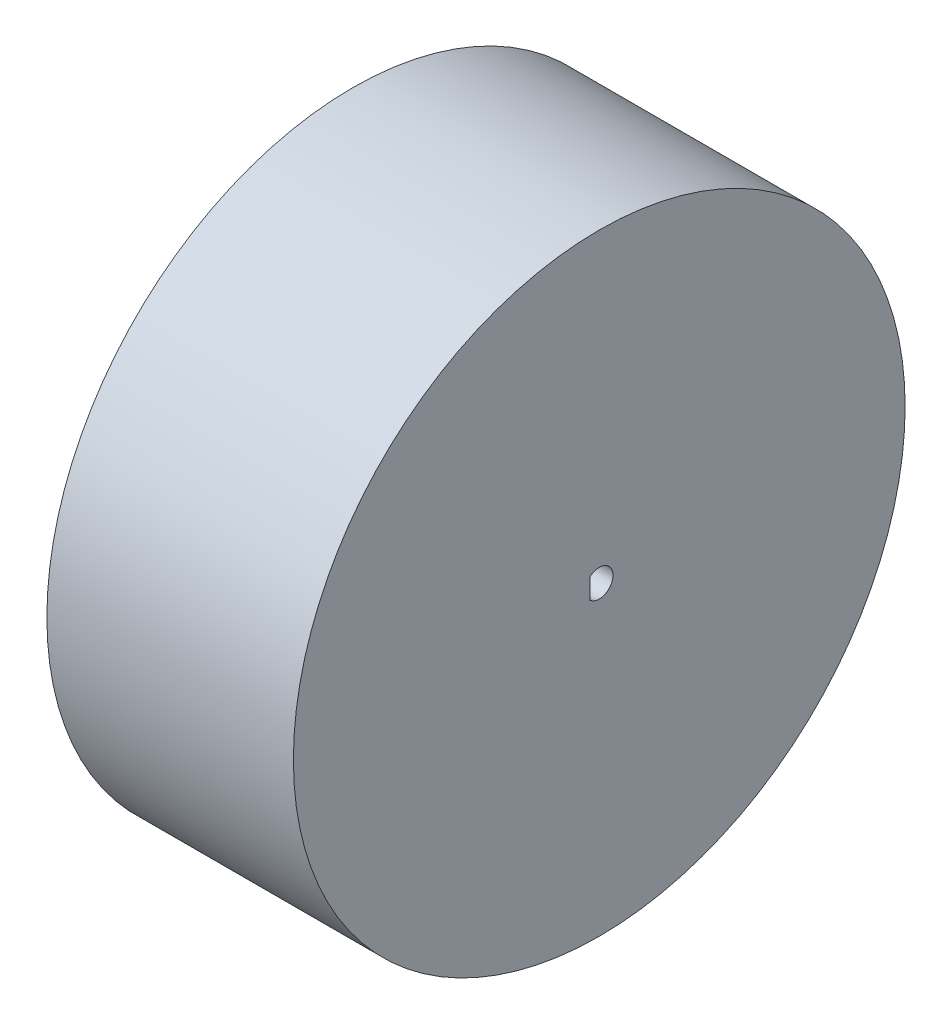
SolidWorks part; units mm, degrees
ref_plane "Front Plane" through (0, 0, 0) normal (0, 0, 1) x (1, 0, 0)
ref_plane "Top Plane" through (0, 0, 0) normal (0, 1, 0) x (1, 0, 0)
ref_plane "Right Plane" through (0, 0, 0) normal (1, 0, 0) x (0, 0, -1)
sketch "Sketch1" plane through (0, 0, 0) normal (1, 0, 0) x (0, 0, -1)
  line L0 (-1, 1.118) -> (-1, -1.118)
  circle A0 centre (0, 0) radius 33.5
  arc A1 (-1, -1.118) -> (-1, 1.118) centre (0, 0) ccw
  dimension "D1" = 67
  dimension "D2" = 1.5
  dimension "D3" = 1
extrude "Boss-Extrude1" add sketch "Sketch1" along normal blind 27
